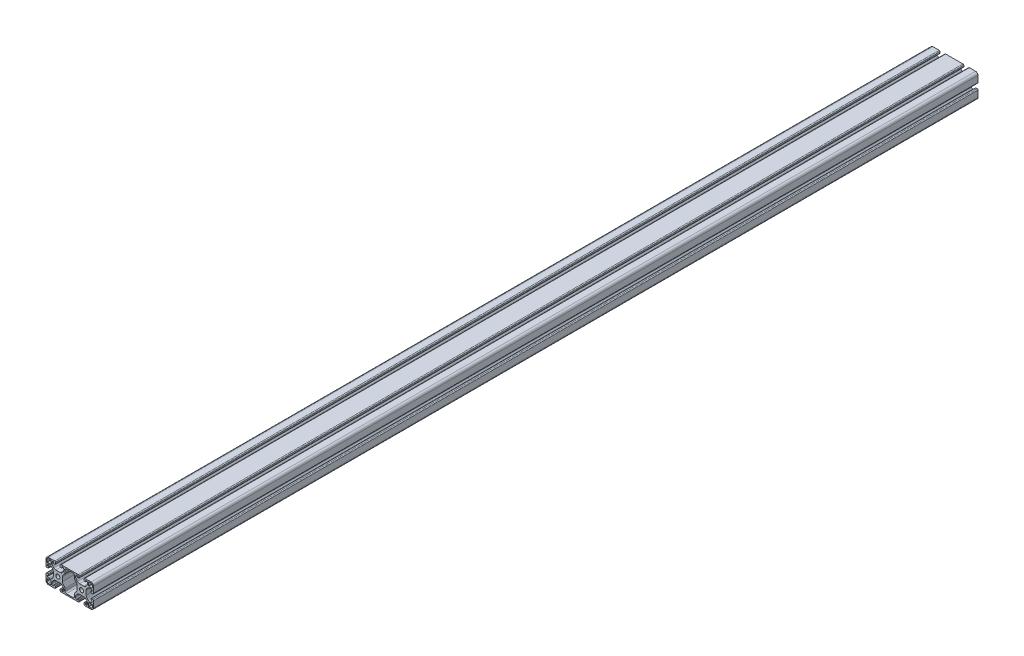
SolidWorks part; units mm, degrees
ref_plane "Plan de face" through (0, 0, 0) normal (0, 0, 1) x (1, 0, 0)
ref_plane "Plan de dessus" through (0, 0, 0) normal (0, 1, 0) x (1, 0, 0)
ref_plane "Plan de droite" through (0, 0, 0) normal (1, 0, 0) x (0, 0, -1)
ref_plane "Plan1" through (0, 0, 20) normal (0, 0, 1) x (1, 0, 0)
sketch "Esquisse1" plane through (0, 0, 20) normal (0, 0, 1) x (1, 0, 0)
  line L0 (66.5, 4.5) -> (65, 4.5)
  line L1 (64, 3.5) -> (64, 1.5)
  line L2 (65.5, 0) -> (76, 0)
  line L3 (80, 4) -> (80, 14.5)
  line L4 (78.5, 16) -> (76.5, 16)
  line L5 (75.5, 15) -> (75.5, 13.5)
  line L6 (76, 13) -> (77.5, 13)
  line L7 (75.5, 10) -> (74.1924, 10)
  line L8 (70.6569, 11.4645) -> (69.2145, 12.9069)
  line L9 (67.75, 16.4424) -> (67.75, 23.5576)
  line L10 (69.2145, 27.0931) -> (70.6569, 28.5355)
  line L11 (74.1924, 30) -> (75.5, 30)
  line L12 (77.5, 27) -> (76, 27)
  line L13 (75.5, 26.5) -> (75.5, 25)
  line L14 (76.5, 24) -> (78.5, 24)
  line L15 (80, 25.5) -> (80, 36)
  line L16 (76, 40) -> (65.5, 40)
  line L17 (64, 38.5) -> (64, 36.5)
  line L18 (65, 35.5) -> (66.5, 35.5)
  line L19 (67, 36) -> (67, 37.5)
  line L20 (70, 35.5) -> (70, 34.1924)
  line L21 (68.5355, 30.6569) -> (67.0931, 29.2145)
  line L22 (63.5576, 27.75) -> (56.4424, 27.75)
  line L23 (52.9069, 29.2145) -> (51.4645, 30.6569)
  line L24 (50, 34.1924) -> (50, 35.5)
  line L25 (53, 37.5) -> (53, 36)
  line L26 (53.5, 35.5) -> (55, 35.5)
  line L27 (56, 36.5) -> (56, 38.5)
  line L28 (54.5, 40) -> (25.5, 40)
  line L29 (24, 38.5) -> (24, 36.5)
  line L30 (25, 35.5) -> (26.5, 35.5)
  line L31 (27, 36) -> (27, 37.5)
  line L32 (30, 35.5) -> (30, 34.1924)
  line L33 (28.5355, 30.6569) -> (27.0931, 29.2145)
  line L34 (23.5576, 27.75) -> (16.4424, 27.75)
  line L35 (12.9069, 29.2145) -> (11.4645, 30.6569)
  line L36 (10, 34.1924) -> (10, 35.5)
  line L37 (13, 37.5) -> (13, 36)
  line L38 (13.5, 35.5) -> (15, 35.5)
  line L39 (16, 36.5) -> (16, 38.5)
  line L40 (14.5, 40) -> (4, 40)
  line L41 (0, 36) -> (0, 25.5)
  line L42 (1.5, 24) -> (3.5, 24)
  line L43 (4.5, 25) -> (4.5, 26.5)
  line L44 (4, 27) -> (2.5, 27)
  line L45 (4.5, 30) -> (5.8076, 30)
  line L46 (9.3431, 28.5355) -> (10.7855, 27.0931)
  line L47 (12.25, 23.5576) -> (12.25, 16.4424)
  line L48 (10.7855, 12.9069) -> (9.3431, 11.4645)
  line L49 (5.8076, 10) -> (4.5, 10)
  line L50 (2.5, 13) -> (4, 13)
  line L51 (4.5, 13.5) -> (4.5, 15)
  line L52 (3.5, 16) -> (1.5, 16)
  line L53 (0, 14.5) -> (0, 4)
  line L54 (4, 0) -> (14.5, 0)
  line L55 (16, 1.5) -> (16, 3.5)
  line L56 (15, 4.5) -> (13.5, 4.5)
  line L57 (13, 4) -> (13, 2.5)
  line L58 (10, 4.5) -> (10, 5.8076)
  line L59 (11.4645, 9.3431) -> (12.9069, 10.7855)
  line L60 (16.4424, 12.25) -> (23.5576, 12.25)
  line L61 (27.0931, 10.7855) -> (28.5355, 9.3431)
  line L62 (30, 5.8076) -> (30, 4.5)
  line L63 (27, 2.5) -> (27, 4)
  line L64 (26.5, 4.5) -> (25, 4.5)
  line L65 (24, 3.5) -> (24, 1.5)
  line L66 (25.5, 0) -> (54.5, 0)
  line L67 (56, 1.5) -> (56, 3.5)
  line L68 (55, 4.5) -> (53.5, 4.5)
  line L69 (53, 4) -> (53, 2.5)
  line L70 (50, 4.5) -> (50, 5.8076)
  line L71 (51.4645, 9.3431) -> (52.9069, 10.7855)
  line L72 (56.4424, 12.25) -> (63.5576, 12.25)
  line L73 (67.0931, 10.7855) -> (68.5355, 9.3431)
  line L74 (70, 5.8076) -> (70, 4.5)
  line L75 (67, 2.5) -> (67, 4)
  line L76 (31.8, 4.5) -> (31.8, 8.2503)
  line L77 (30.3355, 11.7858) -> (29.2145, 12.9069)
  line L78 (27.75, 16.4424) -> (27.75, 23.5576)
  line L79 (29.2145, 27.0931) -> (30.3355, 28.2142)
  line L80 (31.8, 31.7497) -> (31.8, 35.5)
  line L81 (34.3, 38) -> (45.7, 38)
  line L82 (48.2, 35.5) -> (48.2, 31.7497)
  line L83 (49.6645, 28.2142) -> (50.7855, 27.0931)
  line L84 (52.25, 23.5576) -> (52.25, 16.4424)
  line L85 (50.7855, 12.9069) -> (49.6645, 11.7858)
  line L86 (48.2, 8.2503) -> (48.2, 4.5)
  line L87 (45.7, 2) -> (34.3, 2)
  line L88 (7.7, 1.8) -> (4, 1.8)
  line L89 (1.8, 4) -> (1.8, 7.7)
  line L90 (2.3, 8.2) -> (7.7, 8.2)
  line L91 (8.2, 7.7) -> (8.2, 2.3)
  line L92 (72.3, 38.2) -> (76, 38.2)
  line L93 (78.2, 36) -> (78.2, 32.3)
  line L94 (77.7, 31.8) -> (72.3, 31.8)
  line L95 (71.8, 32.3) -> (71.8, 37.7)
  line L96 (78.2, 7.7) -> (78.2, 4)
  line L97 (76, 1.8) -> (72.3, 1.8)
  line L98 (71.8, 2.3) -> (71.8, 7.7)
  line L99 (72.3, 8.2) -> (77.7, 8.2)
  line L100 (1.8, 32.3) -> (1.8, 36)
  line L101 (4, 38.2) -> (7.7, 38.2)
  line L102 (8.2, 37.7) -> (8.2, 32.3)
  line L103 (7.7, 31.8) -> (2.3, 31.8)
  arc A0 (67, 4) -> (66.5, 4.5) centre (66.5, 4) ccw
  arc A1 (65, 4.5) -> (64, 3.5) centre (65, 3.5) ccw
  arc A2 (64, 1.5) -> (65.5, 0) centre (65.5, 1.5) ccw
  arc A3 (76, 0) -> (80, 4) centre (76, 4) ccw
  arc A4 (80, 14.5) -> (78.5, 16) centre (78.5, 14.5) ccw
  arc A5 (76.5, 16) -> (75.5, 15) centre (76.5, 15) ccw
  arc A6 (75.5, 13.5) -> (76, 13) centre (76, 13.5) ccw
  arc A7 (77.5, 13) -> (78, 12.5) centre (77.5, 12.5) cw
  arc A8 (78, 12.5) -> (75.5, 10) centre (75.5, 12.5) cw
  arc A9 (74.1924, 10) -> (70.6569, 11.4645) centre (74.1924, 15) cw
  arc A10 (69.2145, 12.9069) -> (67.75, 16.4424) centre (72.75, 16.4424) cw
  arc A11 (67.75, 23.5576) -> (69.2145, 27.0931) centre (72.75, 23.5576) cw
  arc A12 (70.6569, 28.5355) -> (74.1924, 30) centre (74.1924, 25) cw
  arc A13 (75.5, 30) -> (78, 27.5) centre (75.5, 27.5) cw
  arc A14 (78, 27.5) -> (77.5, 27) centre (77.5, 27.5) cw
  arc A15 (76, 27) -> (75.5, 26.5) centre (76, 26.5) ccw
  arc A16 (75.5, 25) -> (76.5, 24) centre (76.5, 25) ccw
  arc A17 (78.5, 24) -> (80, 25.5) centre (78.5, 25.5) ccw
  arc A18 (80, 36) -> (76, 40) centre (76, 36) ccw
  arc A19 (65.5, 40) -> (64, 38.5) centre (65.5, 38.5) ccw
  arc A20 (64, 36.5) -> (65, 35.5) centre (65, 36.5) ccw
  arc A21 (66.5, 35.5) -> (67, 36) centre (66.5, 36) ccw
  arc A22 (67, 37.5) -> (67.5, 38) centre (67.5, 37.5) cw
  arc A23 (67.5, 38) -> (70, 35.5) centre (67.5, 35.5) cw
  arc A24 (70, 34.1924) -> (68.5355, 30.6569) centre (65, 34.1924) cw
  arc A25 (67.0931, 29.2145) -> (63.5576, 27.75) centre (63.5576, 32.75) cw
  arc A26 (56.4424, 27.75) -> (52.9069, 29.2145) centre (56.4424, 32.75) cw
  arc A27 (51.4645, 30.6569) -> (50, 34.1924) centre (55, 34.1924) cw
  arc A28 (50, 35.5) -> (52.5, 38) centre (52.5, 35.5) cw
  arc A29 (52.5, 38) -> (53, 37.5) centre (52.5, 37.5) cw
  arc A30 (53, 36) -> (53.5, 35.5) centre (53.5, 36) ccw
  arc A31 (55, 35.5) -> (56, 36.5) centre (55, 36.5) ccw
  arc A32 (56, 38.5) -> (54.5, 40) centre (54.5, 38.5) ccw
  arc A33 (25.5, 40) -> (24, 38.5) centre (25.5, 38.5) ccw
  arc A34 (24, 36.5) -> (25, 35.5) centre (25, 36.5) ccw
  arc A35 (26.5, 35.5) -> (27, 36) centre (26.5, 36) ccw
  arc A36 (27, 37.5) -> (27.5, 38) centre (27.5, 37.5) cw
  arc A37 (27.5, 38) -> (30, 35.5) centre (27.5, 35.5) cw
  arc A38 (30, 34.1924) -> (28.5355, 30.6569) centre (25, 34.1924) cw
  arc A39 (27.0931, 29.2145) -> (23.5576, 27.75) centre (23.5576, 32.75) cw
  arc A40 (16.4424, 27.75) -> (12.9069, 29.2145) centre (16.4424, 32.75) cw
  arc A41 (11.4645, 30.6569) -> (10, 34.1924) centre (15, 34.1924) cw
  arc A42 (10, 35.5) -> (12.5, 38) centre (12.5, 35.5) cw
  arc A43 (12.5, 38) -> (13, 37.5) centre (12.5, 37.5) cw
  arc A44 (13, 36) -> (13.5, 35.5) centre (13.5, 36) ccw
  arc A45 (15, 35.5) -> (16, 36.5) centre (15, 36.5) ccw
  arc A46 (16, 38.5) -> (14.5, 40) centre (14.5, 38.5) ccw
  arc A47 (4, 40) -> (0, 36) centre (4, 36) ccw
  arc A48 (0, 25.5) -> (1.5, 24) centre (1.5, 25.5) ccw
  arc A49 (3.5, 24) -> (4.5, 25) centre (3.5, 25) ccw
  arc A50 (4.5, 26.5) -> (4, 27) centre (4, 26.5) ccw
  arc A51 (2.5, 27) -> (2, 27.5) centre (2.5, 27.5) cw
  arc A52 (2, 27.5) -> (4.5, 30) centre (4.5, 27.5) cw
  arc A53 (5.8076, 30) -> (9.3431, 28.5355) centre (5.8076, 25) cw
  arc A54 (10.7855, 27.0931) -> (12.25, 23.5576) centre (7.25, 23.5576) cw
  arc A55 (12.25, 16.4424) -> (10.7855, 12.9069) centre (7.25, 16.4424) cw
  arc A56 (9.3431, 11.4645) -> (5.8076, 10) centre (5.8076, 15) cw
  arc A57 (4.5, 10) -> (2, 12.5) centre (4.5, 12.5) cw
  arc A58 (2, 12.5) -> (2.5, 13) centre (2.5, 12.5) cw
  arc A59 (4, 13) -> (4.5, 13.5) centre (4, 13.5) ccw
  arc A60 (4.5, 15) -> (3.5, 16) centre (3.5, 15) ccw
  arc A61 (1.5, 16) -> (0, 14.5) centre (1.5, 14.5) ccw
  arc A62 (0, 4) -> (4, 0) centre (4, 4) ccw
  arc A63 (14.5, 0) -> (16, 1.5) centre (14.5, 1.5) ccw
  arc A64 (16, 3.5) -> (15, 4.5) centre (15, 3.5) ccw
  arc A65 (13.5, 4.5) -> (13, 4) centre (13.5, 4) ccw
  arc A66 (13, 2.5) -> (12.5, 2) centre (12.5, 2.5) cw
  arc A67 (12.5, 2) -> (10, 4.5) centre (12.5, 4.5) cw
  arc A68 (10, 5.8076) -> (11.4645, 9.3431) centre (15, 5.8076) cw
  arc A69 (12.9069, 10.7855) -> (16.4424, 12.25) centre (16.4424, 7.25) cw
  arc A70 (23.5576, 12.25) -> (27.0931, 10.7855) centre (23.5576, 7.25) cw
  arc A71 (28.5355, 9.3431) -> (30, 5.8076) centre (25, 5.8076) cw
  arc A72 (30, 4.5) -> (27.5, 2) centre (27.5, 4.5) cw
  arc A73 (27.5, 2) -> (27, 2.5) centre (27.5, 2.5) cw
  arc A74 (27, 4) -> (26.5, 4.5) centre (26.5, 4) ccw
  arc A75 (25, 4.5) -> (24, 3.5) centre (25, 3.5) ccw
  arc A76 (24, 1.5) -> (25.5, 0) centre (25.5, 1.5) ccw
  arc A77 (54.5, 0) -> (56, 1.5) centre (54.5, 1.5) ccw
  arc A78 (56, 3.5) -> (55, 4.5) centre (55, 3.5) ccw
  arc A79 (53.5, 4.5) -> (53, 4) centre (53.5, 4) ccw
  arc A80 (53, 2.5) -> (52.5, 2) centre (52.5, 2.5) cw
  arc A81 (52.5, 2) -> (50, 4.5) centre (52.5, 4.5) cw
  arc A82 (50, 5.8076) -> (51.4645, 9.3431) centre (55, 5.8076) cw
  arc A83 (52.9069, 10.7855) -> (56.4424, 12.25) centre (56.4424, 7.25) cw
  arc A84 (63.5576, 12.25) -> (67.0931, 10.7855) centre (63.5576, 7.25) cw
  arc A85 (68.5355, 9.3431) -> (70, 5.8076) centre (65, 5.8076) cw
  arc A86 (70, 4.5) -> (67.5, 2) centre (67.5, 4.5) cw
  arc A87 (67.5, 2) -> (67, 2.5) centre (67.5, 2.5) cw
  circle A88 centre (20, 20) radius 3.4
  circle A89 centre (60, 20) radius 3.4
  arc A90 (34.3, 2) -> (31.8, 4.5) centre (34.3, 4.5) cw
  arc A91 (31.8, 8.2503) -> (30.3355, 11.7858) centre (26.8, 8.2503) ccw
  arc A92 (29.2145, 12.9069) -> (27.75, 16.4424) centre (32.75, 16.4424) cw
  arc A93 (27.75, 23.5576) -> (29.2145, 27.0931) centre (32.75, 23.5576) cw
  arc A94 (30.3355, 28.2142) -> (31.8, 31.7497) centre (26.8, 31.7497) ccw
  arc A95 (31.8, 35.5) -> (34.3, 38) centre (34.3, 35.5) cw
  arc A96 (45.7, 38) -> (48.2, 35.5) centre (45.7, 35.5) cw
  arc A97 (48.2, 31.7497) -> (49.6645, 28.2142) centre (53.2, 31.7497) ccw
  arc A98 (50.7855, 27.0931) -> (52.25, 23.5576) centre (47.25, 23.5576) cw
  arc A99 (52.25, 16.4424) -> (50.7855, 12.9069) centre (47.25, 16.4424) cw
  arc A100 (49.6645, 11.7858) -> (48.2, 8.2503) centre (53.2, 8.2503) ccw
  arc A101 (48.2, 4.5) -> (45.7, 2) centre (45.7, 4.5) cw
  arc A102 (8.2, 2.3) -> (7.7, 1.8) centre (7.7, 2.3) cw
  arc A103 (4, 1.8) -> (1.8, 4) centre (4, 4) cw
  arc A104 (1.8, 7.7) -> (2.3, 8.2) centre (2.3, 7.7) cw
  arc A105 (7.7, 8.2) -> (8.2, 7.7) centre (7.7, 7.7) cw
  arc A106 (71.8, 37.7) -> (72.3, 38.2) centre (72.3, 37.7) cw
  arc A107 (76, 38.2) -> (78.2, 36) centre (76, 36) cw
  arc A108 (78.2, 32.3) -> (77.7, 31.8) centre (77.7, 32.3) cw
  arc A109 (72.3, 31.8) -> (71.8, 32.3) centre (72.3, 32.3) cw
  arc A110 (77.7, 8.2) -> (78.2, 7.7) centre (77.7, 7.7) cw
  arc A111 (78.2, 4) -> (76, 1.8) centre (76, 4) cw
  arc A112 (72.3, 1.8) -> (71.8, 2.3) centre (72.3, 2.3) cw
  arc A113 (71.8, 7.7) -> (72.3, 8.2) centre (72.3, 7.7) cw
  arc A114 (2.3, 31.8) -> (1.8, 32.3) centre (2.3, 32.3) cw
  arc A115 (1.8, 36) -> (4, 38.2) centre (4, 36) cw
  arc A116 (7.7, 38.2) -> (8.2, 37.7) centre (7.7, 37.7) cw
  arc A117 (8.2, 32.3) -> (7.7, 31.8) centre (7.7, 32.3) cw
extrude "Boss.-Extru.1" add sketch "Esquisse1" against normal blind 1492
